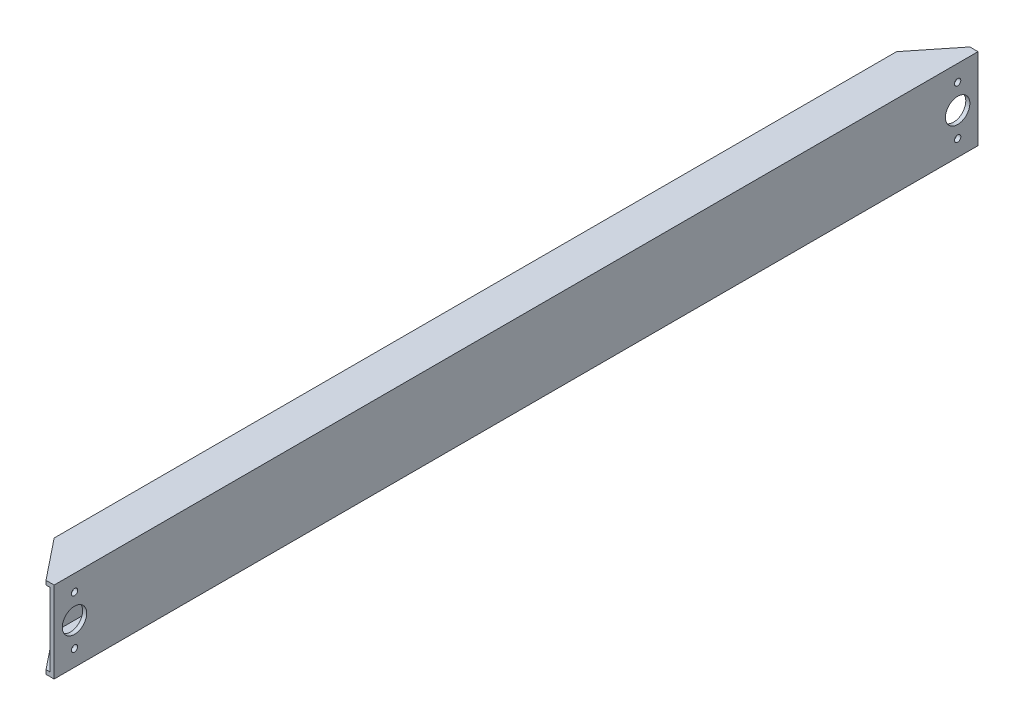
SolidWorks part; units mm, degrees
ref_plane "Front Plane" through (0, 0, 0) normal (0, 0, 1) x (1, 0, 0)
ref_plane "Top Plane" through (0, 0, 0) normal (0, 1, 0) x (1, 0, 0)
ref_plane "Right Plane" through (0, 0, 0) normal (1, 0, 0) x (0, 0, -1)
sketch "Sketch1" plane through (0, 0, 0) normal (0, 0, 1) x (1, 0, 0)
  line L1 (-12.1647, 2.5103) -> (19.5853, 2.5103)
  line L2 (-12.1647, 2.5103) -> (-12.1647, -60.9897)
  line L3 (-12.1647, -60.9897) -> (19.5853, -60.9897)
  line L4 (19.5853, 2.5103) -> (19.5853, -60.9897)
  line L5 (-8.9897, -0.6647) -> (16.4103, -0.6647)
  line L6 (-8.9897, -0.6647) -> (-8.9897, -57.8147)
  line L7 (-8.9897, -57.8147) -> (16.4103, -57.8147)
  line L8 (16.4103, -0.6647) -> (16.4103, -57.8147)
  dimension "D1" = 63.5
  dimension "D2" = 31.75
  dimension "D3" = 3.175
  dimension "D4" = 3.175
  dimension "D5" = 3.175
  dimension "D6" = 3.175
extrude "Boss-Extrude1" add sketch "Sketch1" along normal blind 720.4964
sketch "Sketch2" plane through (0, 2.5103, 0) normal (0, 1, 0) x (1, 0, 0)
  line L0 (13.2353, 0) -> (-12.1647, -31.75)
  line L1 (19.5853, 0) -> (-12.1647, 0) construction
  line L2 (-12.1647, -720.4964) -> (-12.1647, 0) construction
  line L3 (-12.1647, -31.75) -> (-12.1647, 0)
  line L4 (-12.1647, 0) -> (13.2353, 0)
  line L5 (19.5853, -720.4964) -> (19.5853, 0) construction
  line L6 (19.5853, -360.2482) -> (-12.1647, -360.2482)
  line L7 (-12.1647, -720.4964) -> (13.2353, -720.4964)
  line L8 (-12.1647, -688.7464) -> (-12.1647, -720.4964)
  line L9 (13.2353, -720.4964) -> (-12.1647, -688.7464)
  line M4 (19.5853, 0) -> (-12.1647, 0)
  line M5 (-12.1647, 0) -> (-12.1647, -720.4964)
  line M6 (-12.1647, -720.4964) -> (19.5853, -720.4964)
  dimension "D1" = 25.4
  dimension "D2" = 31.75
extrude "Cut-Extrude1" cut sketch "Sketch2" against normal up to surface (63.5 mm away) contours L0 M4 M5 | L9 M6 M5 up to face at (3.7103, -60.9897, 360.2482)
sketch "Sketch3" plane through (16.4103, 0, 0) normal (-1, 0, 0) x (0, 0, 1)
  line L0 (0, -57.8147) -> (0, -0.6647) construction
  line L1 (0, 2.5103) -> (31.75, 2.5103) construction
  line L2 (0, -29.2397) -> (27.7812, -29.2397)
  line L3 (27.7812, -57.8147) -> (27.7812, -0.6647) construction
  line L4 (360.2482, 2.5103) -> (360.2482, -60.9897)
  line L5 (720.4964, -29.2397) -> (692.7151, -29.2397)
  line L6 (688.7464, 2.5103) -> (31.75, 2.5103) construction
  line L7 (688.7464, -60.9897) -> (31.75, -60.9897) construction
  circle A0 centre (15.875, -29.2397) radius 9.525
  circle A1 centre (704.6214, -29.2397) radius 9.525
  point P0 (15.875, -10.1897)
  point P9 (15.875, -48.2897)
  point P22 (704.6214, -48.2897)
  point P23 (704.6214, -10.1897)
  dimension "D1" = 15.875
  dimension "D2" = 12.7
hole_wizard "#10 (0.1935) Diameter Hole1" positions "3DSketch1" profile "Sketch4" hole size "#10" standard "ANSI Inch" end condition through all
sketch3d "3DSketch1"
  point P0 (16.4103, -10.1897, 15.875)
  point P3 (16.4103, -48.2897, 15.875)
  point P6 (16.4103, -10.1897, 704.6214)
  point P9 (16.4103, -48.2897, 704.6214)
sketch "Sketch4" plane through (16.4103, -10.1897, 15.875) normal (0, 1, 0) x (0, 0, 1)
  line L0 (0, 0) -> (0, 3.175)
  line L1 (0, 3.175) -> (2.4574, 3.175)
  line L2 (2.4574, 3.175) -> (2.4574, 0)
  line L5 (2.4574, 0) -> (0, 0)
  line L11 (0, -6.35) -> (0, 107.95) construction
  dimension "Thru Hole Dia." = 4.9149
  dimension "Thru Hole Depth" = 3.175
extrude "Cut-Extrude2" cut sketch "Sketch3" against normal up to surface (3.175 mm away) contours A0 | A1 up to face at (19.5853, -10.1897, 18.3325)
